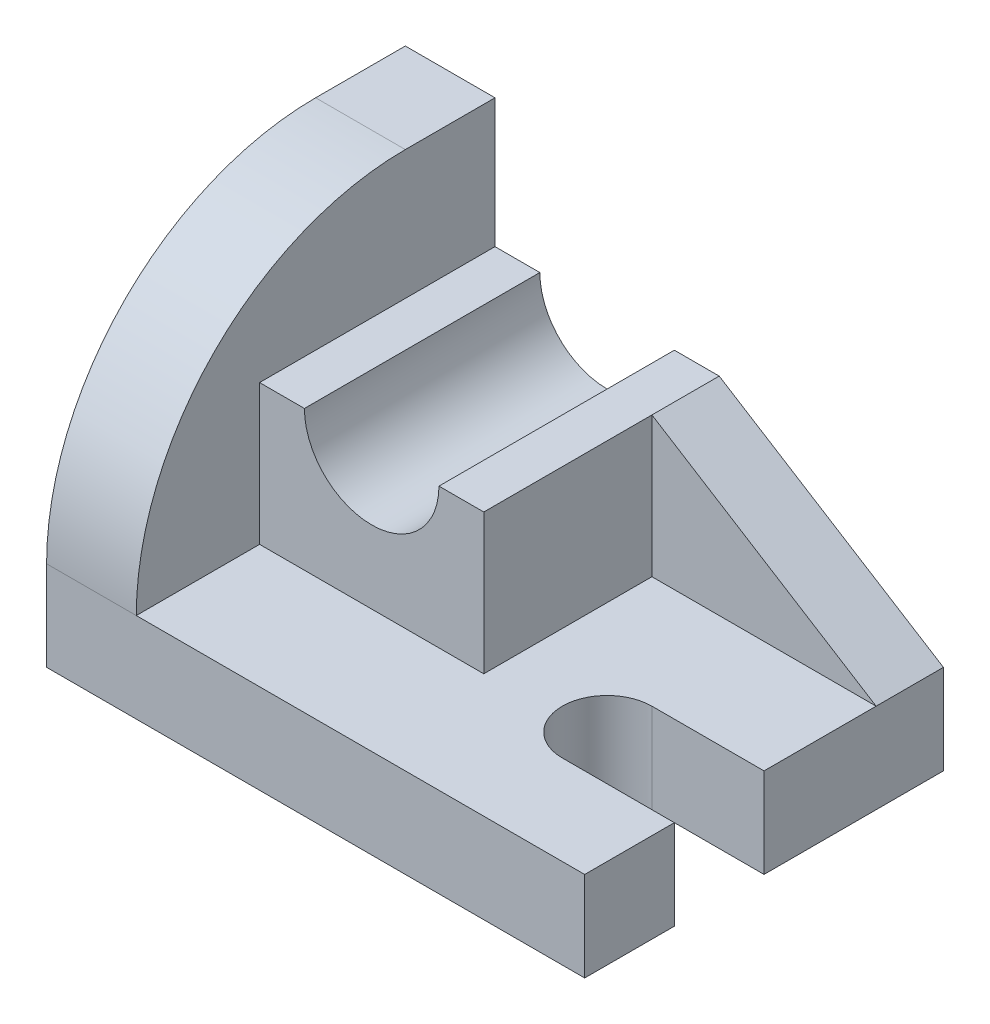
SolidWorks part; units mm, degrees
ref_plane "Front Plane" through (0, 0, 0) normal (0, 0, 1) x (1, 0, 0)
ref_plane "Top Plane" through (0, 0, 0) normal (0, 1, 0) x (1, 0, 0)
ref_plane "Right Plane" through (0, 0, 0) normal (1, 0, 0) x (0, 0, -1)
sketch "Sketch1" plane through (0, 0, 0) normal (0, 1, 0) x (1, 0, 0)
  line L0 (96, 24) -> (76, 24) construction
  line L1 (0, 0) -> (96, 0)
  line L2 (0, 0) -> (0, 64)
  line L3 (0, 64) -> (96, 64)
  line L4 (96, 0) -> (96, 64)
  line L5 (96, 16) -> (76, 16)
  line L6 (96, 32) -> (76, 32)
  arc A0 (96, 16) -> (96, 32) centre (96, 24) ccw
  arc A1 (76, 32) -> (76, 16) centre (76, 24) ccw
  point P7 (86, 24)
  dimension "D4" = 8
  dimension "D1" = 64
  dimension "D2" = 96
  dimension "D3" = 20
  dimension "D5" = 16
extrude "Boss-Extrude1" add sketch "Sketch1" along normal blind 16 contours A1 L6 L4 L3 L2 L1 L5
sketch "Sketch2" plane through (0, 0, 0) normal (-1, 0, 0) x (0, 0, 1)
  line L0 (48, -48) -> (48, 112) construction
  line L1 (0, 0) -> (-64, 0)
  line L2 (0, 0) -> (0, 16)
  line L3 (-48, 64) -> (-64, 64)
  line L4 (-64, 0) -> (-64, 64)
  line L5 (48, 112) -> (-112, 112) construction
  line L6 (-112, -48) -> (-112, 112) construction
  line L7 (48, -48) -> (-112, -48) construction
  line L8 (0, 64) -> (-64, 64) construction
  line L9 (0, 0) -> (0, 64) construction
  arc A0 (-48, 64) -> (0, 16) centre (-48, 16) cw
  point P12 (0, 64)
  dimension "D3" = 48
  dimension "D1" = 64
  dimension "D2" = 64
extrude "Boss-Extrude2" add sketch "Sketch2" against normal blind 16
sketch "Sketch3" plane through (0, 0, -64) normal (0, 0, -1) x (-1, 0, 0)
  line L1 (-16, 16) -> (-56, 16)
  line L2 (-16, 16) -> (-16, 41)
  line L3 (-16, 41) -> (-56, 41)
  line L4 (-56, 16) -> (-56, 41)
  circle A0 centre (-36, 41) radius 12
  line M7 (-16, 64) -> (-16, 16)
  line M8 (-16, 16) -> (-96, 16)
  dimension "D3" = 24
  dimension "D1" = 40
  dimension "D2" = 25
extrude "Boss-Extrude3" add sketch "Sketch3" against normal blind 42 contours A0 L3 L4 M8 M7
sketch "Sketch4" plane through (0, 0, -64) normal (0, 0, -1) x (-1, 0, 0)
  line L0 (-96, 16) -> (-56, 41)
  line L1 (-56, 16) -> (-56, 41) construction
  line L2 (-56, 41) -> (-56, 16)
  line L3 (-56, 16) -> (-96, 16)
extrude "Boss-Extrude4" add sketch "Sketch4" against normal blind 12
